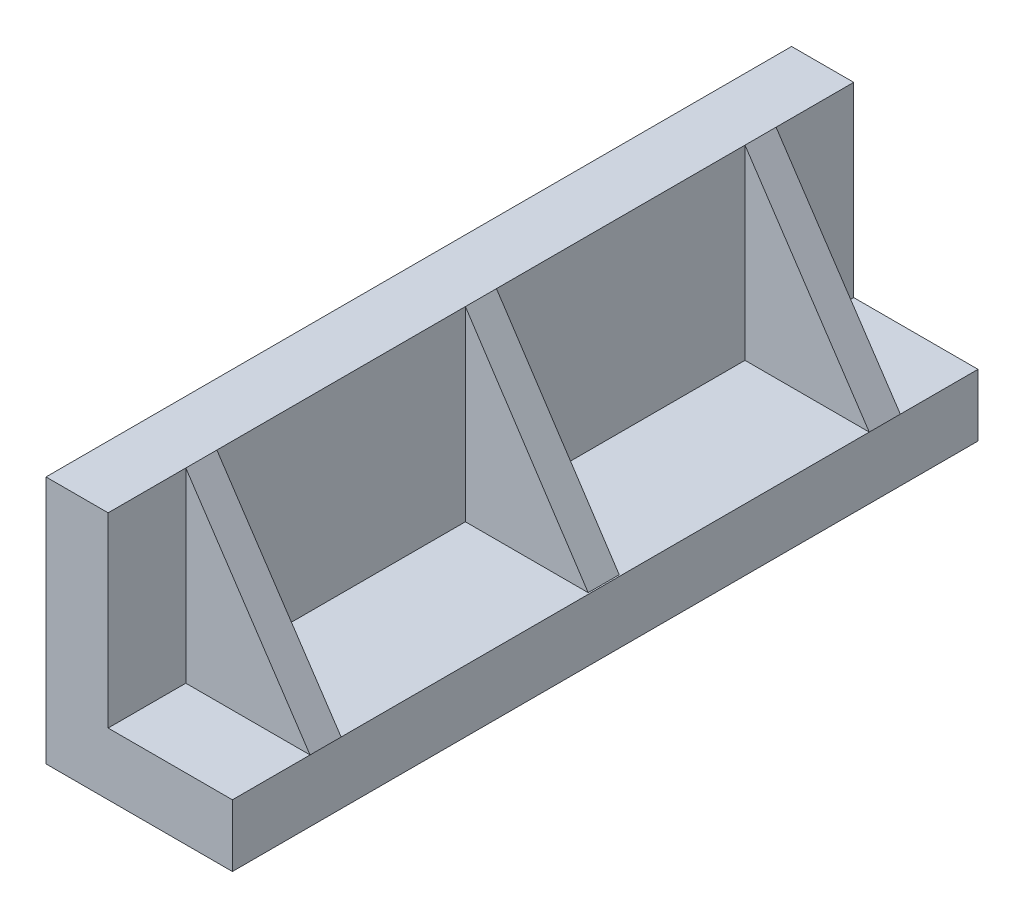
SolidWorks part; units mm, degrees
ref_plane "Front Plane" through (0, 0, 0) normal (0, 0, 1) x (1, 0, 0)
ref_plane "Top Plane" through (0, 0, 0) normal (0, 1, 0) x (1, 0, 0)
ref_plane "Right Plane" through (0, 0, 0) normal (1, 0, 0) x (0, 0, -1)
sketch "Sketch1" plane through (0, 0, 0) normal (0, 0, 1) x (1, 0, 0)
  line L0 (0, 40) -> (0, 0)
  line L1 (0, 0) -> (30, 0)
  line L2 (30, 0) -> (30, 10)
  line L3 (30, 10) -> (10, 10)
  line L4 (10, 10) -> (10, 40)
  line L5 (10, 40) -> (0, 40)
  dimension "D1" = 30
  dimension "D2" = 40
  dimension "D3" = 10
  dimension "D4" = 10
extrude "Boss-Extrude1" add sketch "Sketch1" along normal blind 120
ref_plane "Plane1" through (0, 0, 60) normal (0, 0, 1) x (1, 0, 0)
sketch "Sketch2" plane through (0, 0, 60) normal (0, 0, 1) x (1, 0, 0)
  line L0 (10, 40) -> (29.7588, 10)
  line L1 (10, 10) -> (10, 40) construction
  line L2 (30, 10) -> (10, 10) construction
  point P6 (29.7588, 10)
  point P7 (10, 40)
rib "Rib2" sketch "Sketch2" sketch "Sketch2" thickness 5 extrusion direction parallel to sketch draft on no parameters "D1"=5
ref_plane "Plane2" through (0, 0, 105) normal (0, 0, 1) x (1, 0, 0)
sketch "Sketch3" plane through (0, 0, 105) normal (0, 0, 1) x (1, 0, 0)
  line L0 (10, 40) -> (30, 10)
rib "Rib3" sketch "Sketch3" sketch "Sketch3" thickness 5 extrusion direction parallel to sketch draft on no parameters "D1"=5
ref_plane "Plane3" through (0, 0, 15) normal (0, 0, 1) x (1, 0, 0)
sketch "Sketch4" plane through (0, 0, 15) normal (0, 0, 1) x (1, 0, 0)
  line L0 (10, 40) -> (30, 10)
rib "Rib4" sketch "Sketch4" sketch "Sketch4" thickness 5 extrusion direction parallel to sketch draft on no parameters "D1"=5
